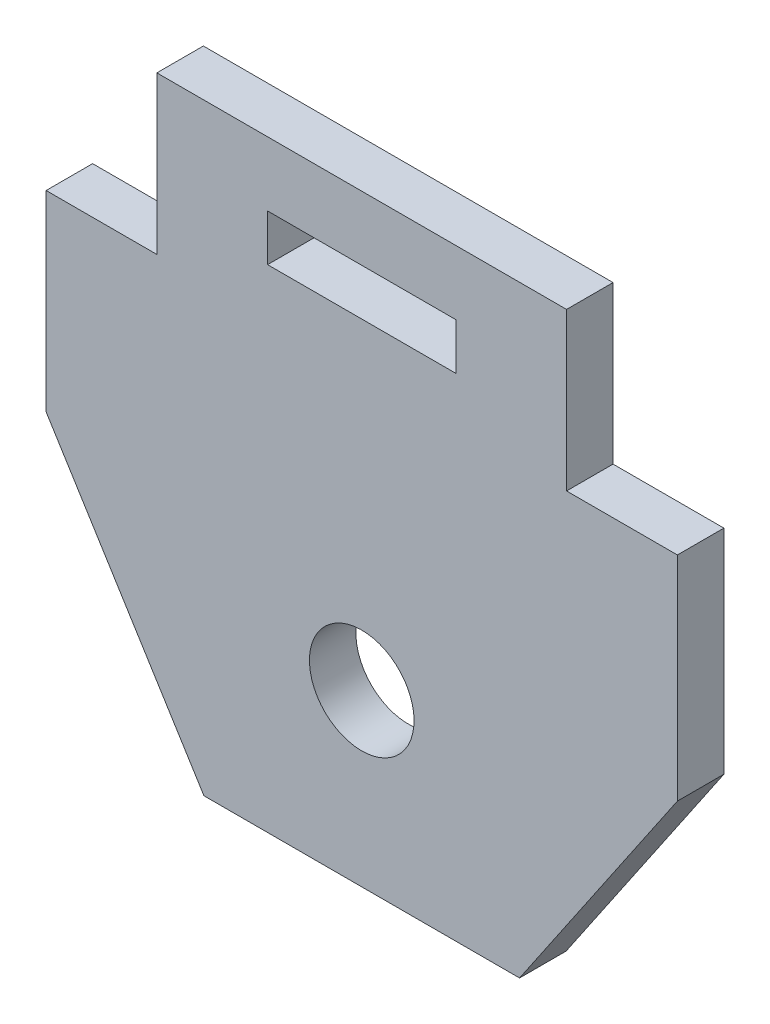
SolidWorks part; units mm, degrees
ref_plane "Front Plane" through (0, 0, 0) normal (0, 0, 1) x (1, 0, 0)
ref_plane "Top Plane" through (0, 0, 0) normal (0, 1, 0) x (1, 0, 0)
ref_plane "Right Plane" through (0, 0, 0) normal (1, 0, 0) x (0, 0, -1)
sketch "Sketch1" plane through (0, 0, 0) normal (0, 0, 1) x (1, 0, 0)
  line L0 (-36.2, 2.4626) -> (0, -26.6191) construction
  line L1 (-36.2, 24.45) -> (-23.5, 24.45)
  line L2 (-36.2, 24.45) -> (-36.2, 2.4626)
  line L3 (-18.1, -26.6191) -> (18.1, -26.6191)
  line L4 (36.2, 24.45) -> (36.2, 0)
  line L5 (-36.2, 24.45) -> (36.2, -24.45) construction
  line L6 (-24.4073, -16.485) -> (36.2, 24.45) construction
  line L7 (0, -26.6191) -> (36.2, 0) construction
  line L8 (-18.1, -12.0782) -> (-18.1, -26.6191) construction
  line L9 (18.1, -13.3095) -> (18.1, -26.6191) construction
  line L10 (-36.2, 2.4626) -> (-18.1, -26.6191) construction
  line L11 (36.2, 0) -> (18.1, -26.6191) construction
  line L12 (-36.2, 2.4626) -> (-18.1, -26.6191)
  line L13 (18.1, -26.6191) -> (36.2, 0)
  line L14 (-36.2, 24.45) -> (-36.2, 34.5878) construction
  line L15 (-36.2, 34.5878) -> (-23.5, 34.5878) construction
  line L16 (23.49, 24.45) -> (36.2, 24.45)
  line L18 (-23.5, 24.45) -> (-23.5, 42.484)
  line L19 (-23.5, 42.484) -> (23.49, 42.484)
  line L20 (23.49, 24.45) -> (23.49, 42.484)
  line L21 (10.79, 24.45) -> (10.79, 29.784) construction
  line L23 (10.79, 29.784) -> (-10.8, 29.784)
  line L24 (10.79, 29.784) -> (10.79, 35.118)
  line L25 (10.79, 35.118) -> (-10.8, 35.118)
  line L26 (-10.8, 29.784) -> (-10.8, 35.118)
  point P0 (0, 0)
  dimension "D2" = 48.9
  dimension "D3" = 12.7
  dimension "D4" = 46.99
  dimension "D5" = 18.034
  dimension "D6" = 5.334
  dimension "D7" = 21.59
  dimension "D8" = 5.334
  dimension "D9" = 5.334
extrude "Boss-Extrude1" add sketch "Sketch1" along normal blind 5.334
sketch "Sketch2" plane through (0, 0, 5.334) normal (0, 0, 1) x (1, 0, 0)
  line L0 (-0.005, 29.784) -> (0, -7.112) construction
  line L2 (-10.8, 29.784) -> (10.79, 29.784) construction
  circle A0 centre (0, -7.112) radius 6
  dimension "D1" = 12
  dimension "D2" = 36.896
extrude "Cut-Extrude1" cut sketch "Sketch2" against normal blind 5.334
